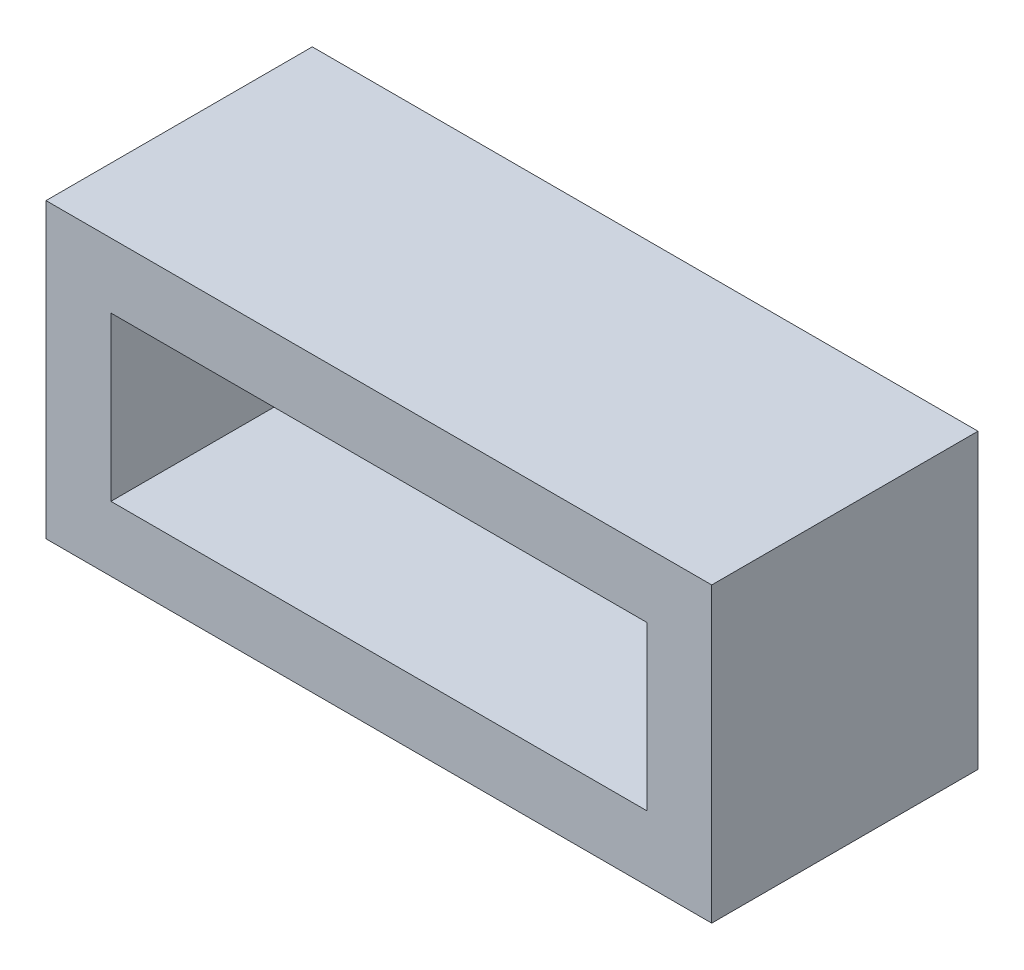
SolidWorks part; units mm, degrees
ref_plane "Front Plane" through (0, 0, 0) normal (0, 0, 1) x (1, 0, 0)
ref_plane "Top Plane" through (0, 0, 0) normal (0, 1, 0) x (1, 0, 0)
ref_plane "Right Plane" through (0, 0, 0) normal (1, 0, 0) x (0, 0, -1)
sketch "Sketch1" plane through (0, 0, 0) normal (0, 0, 1) x (1, 0, 0)
  line L1 (-10.0625, -3.0625) -> (10.0625, -3.0625)
  line L2 (-10.0625, -3.0625) -> (-10.0625, 3.0625)
  line L3 (-10.0625, 3.0625) -> (10.0625, 3.0625)
  line L4 (10.0625, -3.0625) -> (10.0625, 3.0625)
  line L5 (-10.0625, -3.0625) -> (10.0625, 3.0625) construction
  line L6 (-10.0625, 3.0625) -> (10.0625, -3.0625) construction
  line L7 (-12.5, -5.5) -> (12.5, -5.5)
  line L8 (-12.5, -5.5) -> (-12.5, 5.5)
  line L9 (-12.5, 5.5) -> (12.5, 5.5)
  line L10 (12.5, -5.5) -> (12.5, 5.5)
  line L11 (-12.5, -5.5) -> (12.5, 5.5) construction
  line L12 (-12.5, 5.5) -> (12.5, -5.5) construction
  point P0 (0, 0)
  point P6 (0, 0)
  dimension "D1" = 20.125
  dimension "D2" = 6.125
  dimension "D3" = 25
  dimension "D4" = 11
extrude "Boss-Extrude1" add sketch "Sketch1" along normal blind 10
